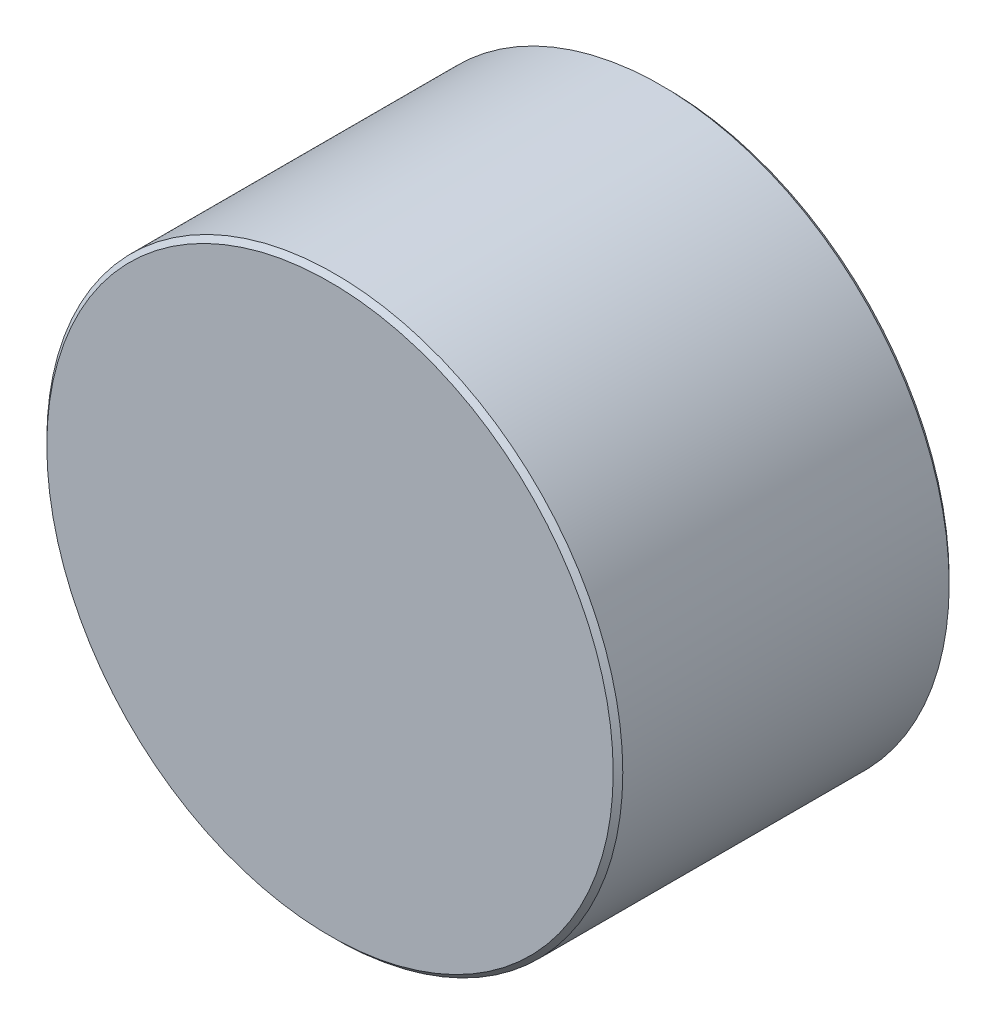
SolidWorks part; units mm, degrees
material "Brass"
ref_plane "Front Plane" through (0, 0, 0) normal (0, 0, 1) x (1, 0, 0)
ref_plane "Top Plane" through (0, 0, 0) normal (0, 1, 0) x (1, 0, 0)
ref_plane "Right Plane" through (0, 0, 0) normal (1, 0, 0) x (0, 0, -1)
sketch "Sketch1" plane through (0, 0, 0) normal (0, 0, 1) x (1, 0, 0)
  circle A0 centre (0, 0) radius 6
  circle A1 centre (0, 0) radius 6 construction
extrude "Boss-Extrude1" add sketch "Sketch1" along normal blind 7
chamfer "Chamfer1" distance 0.1 angle 45 2 edges at (6, 0, 0) (6, 0, 7)
